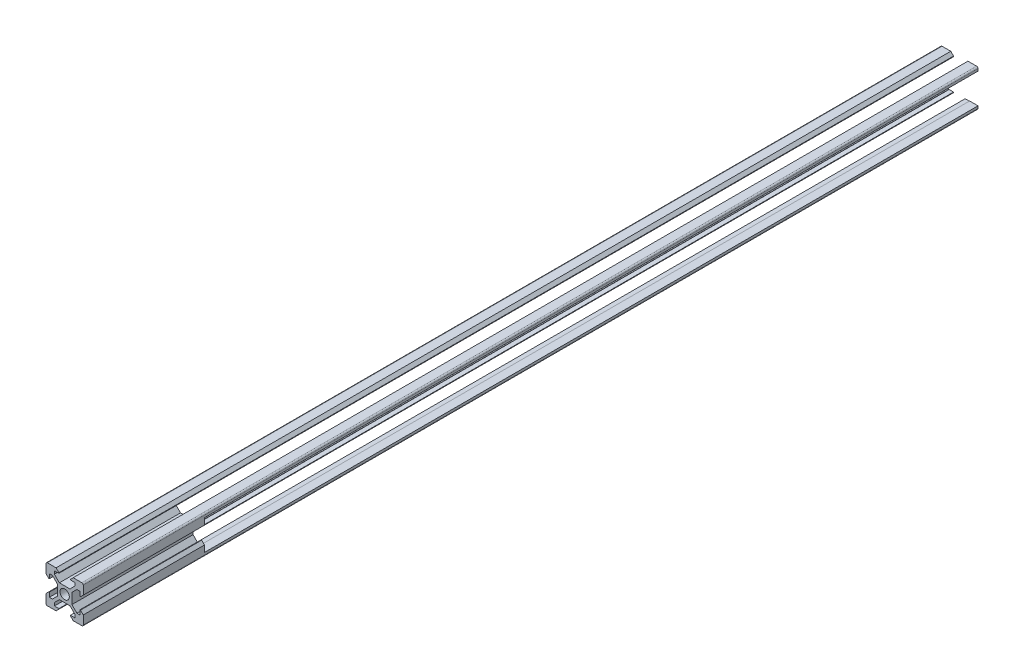
SolidWorks part; units mm, degrees
other "Markup1"
sketch "Sketch1" plane through (10, 10, 480) normal (0.5774, 0.5773, 0.5774) x (0.7071, 0, -0.7071)
ref_plane "Alzado" through (0, 0, 0) normal (0, 0, 1) x (1, 0, 0)
ref_plane "Planta" through (0, 0, 0) normal (0, 1, 0) x (1, 0, 0)
ref_plane "Vista lateral" through (0, 0, 0) normal (1, 0, 0) x (0, 0, -1)
sketch "Croquis1" plane through (0, 0, 0) normal (0, 0, 1) x (1, 0, 0)
  line L0 (-4.6, 10) -> (-3.1, 8.5)
  line L3 (-4.6, 10) -> (-9.25, 10)
  line L5 (-3.1, 8.5) -> (-3.1, 8.2)
  line L6 (-3.1, 8.2) -> (-5.5, 8.2)
  line L7 (-5.5, 8.2) -> (-5.5, 6.5607)
  line L8 (-5.5, 6.5607) -> (-2.84, 3.9007)
  line L9 (-2.84, 3.9007) -> (0, 3.9007)
  line L10 (0, 0) -> (-15.3499, 15.3499) construction
  line L11 (-3.9007, 2.84) -> (-3.9007, 0)
  line L12 (-6.5607, 5.5) -> (-3.9007, 2.84)
  line L13 (-8.2, 5.5) -> (-6.5607, 5.5)
  line L14 (-8.2, 3.1) -> (-8.2, 5.5)
  line L15 (-8.5, 3.1) -> (-8.2, 3.1)
  line L16 (-10, 4.6) -> (-10, 9.25)
  line L17 (-10, 4.6) -> (-8.5, 3.1)
  line L18 (10, 4.6) -> (8.5, 3.1)
  line L19 (10, 4.6) -> (10, 9.25)
  line L20 (8.5, 3.1) -> (8.2, 3.1)
  line L21 (8.2, 3.1) -> (8.2, 5.5)
  line L22 (8.2, 5.5) -> (6.5607, 5.5)
  line L23 (6.5607, 5.5) -> (3.9007, 2.84)
  line L24 (3.9007, 2.84) -> (3.9007, 0)
  line L25 (5.5, 6.5607) -> (2.84, 3.9007)
  line L26 (5.5, 8.2) -> (5.5, 6.5607)
  line L27 (3.1, 8.2) -> (5.5, 8.2)
  line L28 (3.1, 8.5) -> (3.1, 8.2)
  line L29 (4.6, 10) -> (9.25, 10)
  line L30 (4.6, 10) -> (3.1, 8.5)
  line L31 (2.84, 3.9007) -> (0, 3.9007)
  line L32 (4.6, -10) -> (3.1, -8.5)
  line L33 (4.6, -10) -> (9.25, -10)
  line L34 (3.1, -8.5) -> (3.1, -8.2)
  line L35 (3.1, -8.2) -> (5.5, -8.2)
  line L36 (5.5, -8.2) -> (5.5, -6.5607)
  line L37 (5.5, -6.5607) -> (2.84, -3.9007)
  line L38 (2.84, -3.9007) -> (0, -3.9007)
  line L39 (6.5607, -5.5) -> (3.9007, -2.84)
  line L40 (8.2, -5.5) -> (6.5607, -5.5)
  line L41 (8.2, -3.1) -> (8.2, -5.5)
  line L42 (8.5, -3.1) -> (8.2, -3.1)
  line L43 (10, -4.6) -> (10, -9.25)
  line L44 (10, -4.6) -> (8.5, -3.1)
  line L45 (3.9007, -2.84) -> (3.9007, 0)
  line L46 (-10, -4.6) -> (-8.5, -3.1)
  line L47 (-10, -4.6) -> (-10, -9.25)
  line L48 (-8.5, -3.1) -> (-8.2, -3.1)
  line L49 (-8.2, -3.1) -> (-8.2, -5.5)
  line L50 (-8.2, -5.5) -> (-6.5607, -5.5)
  line L51 (-6.5607, -5.5) -> (-3.9007, -2.84)
  line L52 (-3.9007, -2.84) -> (-3.9007, 0)
  line L53 (-5.5, -6.5607) -> (-2.84, -3.9007)
  line L54 (-5.5, -8.2) -> (-5.5, -6.5607)
  line L55 (-3.1, -8.2) -> (-5.5, -8.2)
  line L56 (-3.1, -8.5) -> (-3.1, -8.2)
  line L57 (-4.6, -10) -> (-9.25, -10)
  line L58 (-4.6, -10) -> (-3.1, -8.5)
  line L59 (-2.84, -3.9007) -> (0, -3.9007)
  circle A0 centre (0, 0) radius 2.5
  arc A1 (-9.25, 10) -> (-10, 9.25) centre (-9.25, 9.25) ccw
  arc A2 (10, 9.25) -> (9.25, 10) centre (9.25, 9.25) ccw
  arc A3 (9.25, -10) -> (10, -9.25) centre (9.25, -9.25) ccw
  arc A4 (-10, -9.25) -> (-9.25, -10) centre (-9.25, -9.25) ccw
  point P18 (-10, 10)
  point P37 (10, 10)
  point P55 (10, -10)
  point P73 (-10, -10)
  point P79 (0, 0)
  dimension "D1" = 5
  dimension "D5" = 0.75
  dimension "D2" = 10
  dimension "D3" = 10
  dimension "D4" = 4.6
  dimension "D6" = 5.5
  dimension "D7" = 135
  dimension "D8" = 0.75
  dimension "D9" = 225
  dimension "D10" = 2.84
  dimension "D11" = 1.8
  dimension "D12" = 3.1
  dimension "D13" = 4
extrude "Saliente-Extruir1" add sketch "Croquis1" along normal blind 480
sketch "Sketch2" plane through (0, 0, 0) normal (1, 0, 0) x (0, 0, -1)
  line L0 (-415, 49.0269) -> (-415, -60.8966) construction
  line L1 (-415, -8.0607) -> (415, -8.0607)
  line L2 (-415, -8.0607) -> (-415, 8.0607)
  line L3 (-415, 8.0607) -> (415, 8.0607)
  line L4 (415, -8.0607) -> (415, 8.0607)
  line L5 (-415, -8.0607) -> (415, 8.0607) construction
  line L6 (-415, 8.0607) -> (415, -8.0607) construction
  line L7 (-480, -2.84) -> (-480, 2.84) construction
  point P0 (0, 0)
  dimension "D1" = 65
extrude "Cut-Extrude1" cut sketch "Sketch2" against normal blind 46 and the other way blind 47 contours L2 L1 L4 L3
